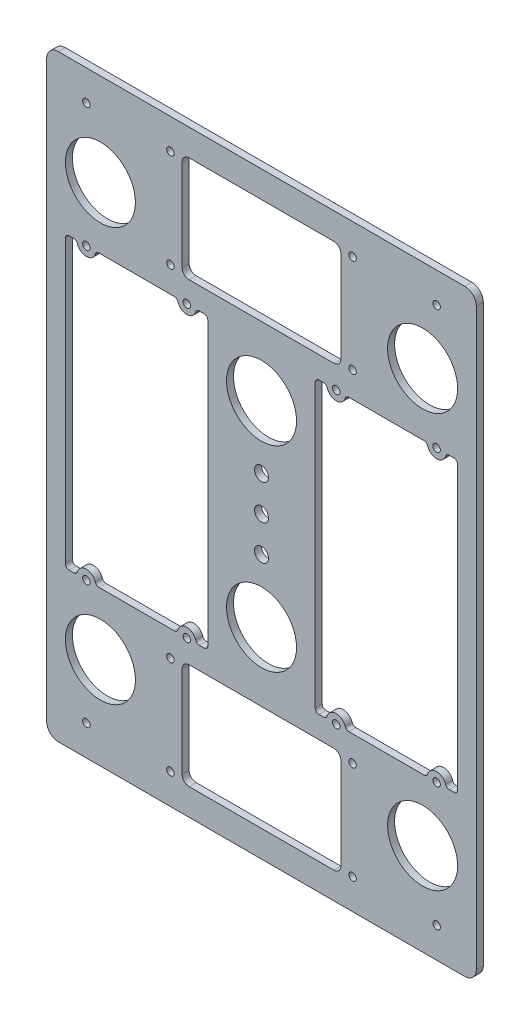
SolidWorks part; units mm, degrees
material "Thornel Mat VMA"
ref_plane "Front Plane" through (0, 0, 0) normal (0, 0, 1) x (1, 0, 0)
ref_plane "Top Plane" through (0, 0, 0) normal (0, 1, 0) x (1, 0, 0)
ref_plane "Right Plane" through (0, 0, 0) normal (1, 0, 0) x (0, 0, -1)
sketch "Model" plane through (0, 0, 0) normal (0, 0, 1) x (1, 0, 0)
  line L0 (-80.3666, 62) -> (-82.4, 62)
  line L1 (-84, 60.4) -> (-84, -60.4)
  line L2 (-82.4, -62) -> (-80.3666, -62)
  line L3 (-69.6334, 62) -> (-37.3666, 62)
  line L4 (-26.6334, 62) -> (-24.6, 62)
  line L5 (-23, 60.4) -> (-23, -60.4)
  line L6 (-24.6, -62) -> (-26.6334, -62)
  line L7 (-69.6334, -62) -> (-37.3666, -62)
  line L8 (26.6334, 62) -> (24.6, 62)
  line L9 (23, 60.4) -> (23, -60.4)
  line L10 (24.6, -62) -> (26.6334, -62)
  line L11 (37.3666, 62) -> (69.6334, 62)
  line L12 (80.3666, 62) -> (82.4, 62)
  line L13 (84, 60.4) -> (84, -60.4)
  line L14 (82.4, -62) -> (80.3666, -62)
  line L15 (37.3666, -62) -> (69.6334, -62)
  line L16 (34, 113.6) -> (34, 74.4)
  line L17 (31, 71.4) -> (-31, 71.4)
  line L18 (31, 116.6) -> (-31, 116.6)
  line L19 (-34, 74.4) -> (-34, 113.6)
  line L20 (34, -113.6) -> (34, -74.4)
  line L21 (31, -71.4) -> (-31, -71.4)
  line L22 (31, -116.6) -> (-31, -116.6)
  line L23 (-34, -74.4) -> (-34, -113.6)
  line L24 (-87, -128) -> (87, -128)
  line L25 (92, -123) -> (92, 123)
  line L26 (87, 128) -> (-87, 128)
  line L27 (-92, 123) -> (-92, -123)
  circle A0 centre (-75, 62) radius 1.6
  circle A1 centre (-32, 62) radius 1.6
  circle A2 centre (-75, -62) radius 1.6
  circle A3 centre (-32, -62) radius 1.6
  arc A4 (-78.8333, 60.8571) -> (-71.1667, 60.8571) centre (-75, 62) ccw
  arc A5 (-69.6334, 62) -> (-71.1667, 60.8571) centre (-69.6334, 60.4) ccw
  arc A6 (-78.8333, 60.8571) -> (-80.3666, 62) centre (-80.3666, 60.4) ccw
  arc A7 (-35.8333, 60.8571) -> (-28.1667, 60.8571) centre (-32, 62) ccw
  arc A8 (-26.6334, 62) -> (-28.1667, 60.8571) centre (-26.6334, 60.4) ccw
  arc A9 (-35.8333, 60.8571) -> (-37.3666, 62) centre (-37.3666, 60.4) ccw
  arc A10 (-71.1667, -60.8571) -> (-78.8333, -60.8571) centre (-75, -62) ccw
  arc A11 (-71.1667, -60.8571) -> (-69.6334, -62) centre (-69.6334, -60.4) ccw
  arc A12 (-80.3666, -62) -> (-78.8333, -60.8571) centre (-80.3666, -60.4) ccw
  arc A13 (-28.1667, -60.8571) -> (-35.8333, -60.8571) centre (-32, -62) ccw
  arc A14 (-28.1667, -60.8571) -> (-26.6334, -62) centre (-26.6334, -60.4) ccw
  arc A15 (-37.3666, -62) -> (-35.8333, -60.8571) centre (-37.3666, -60.4) ccw
  arc A16 (-84, -60.4) -> (-82.4, -62) centre (-82.4, -60.4) ccw
  arc A17 (-82.4, 62) -> (-84, 60.4) centre (-82.4, 60.4) ccw
  arc A18 (-24.6, -62) -> (-23, -60.4) centre (-24.6, -60.4) ccw
  arc A19 (-23, 60.4) -> (-24.6, 62) centre (-24.6, 60.4) ccw
  circle A20 centre (32, 62) radius 1.6
  circle A21 centre (75, 62) radius 1.6
  circle A22 centre (32, -62) radius 1.6
  circle A23 centre (75, -62) radius 1.6
  arc A24 (28.1667, 60.8571) -> (35.8333, 60.8571) centre (32, 62) ccw
  arc A25 (37.3666, 62) -> (35.8333, 60.8571) centre (37.3666, 60.4) ccw
  arc A26 (28.1667, 60.8571) -> (26.6334, 62) centre (26.6334, 60.4) ccw
  arc A27 (71.1667, 60.8571) -> (78.8333, 60.8571) centre (75, 62) ccw
  arc A28 (80.3666, 62) -> (78.8333, 60.8571) centre (80.3666, 60.4) ccw
  arc A29 (71.1667, 60.8571) -> (69.6334, 62) centre (69.6334, 60.4) ccw
  arc A30 (35.8333, -60.8571) -> (28.1667, -60.8571) centre (32, -62) ccw
  arc A31 (35.8333, -60.8571) -> (37.3666, -62) centre (37.3666, -60.4) ccw
  arc A32 (26.6334, -62) -> (28.1667, -60.8571) centre (26.6334, -60.4) ccw
  arc A33 (78.8333, -60.8571) -> (71.1667, -60.8571) centre (75, -62) ccw
  arc A34 (78.8333, -60.8571) -> (80.3666, -62) centre (80.3666, -60.4) ccw
  arc A35 (69.6334, -62) -> (71.1667, -60.8571) centre (69.6334, -60.4) ccw
  arc A36 (23, -60.4) -> (24.6, -62) centre (24.6, -60.4) ccw
  arc A37 (24.6, 62) -> (23, 60.4) centre (24.6, 60.4) ccw
  arc A38 (82.4, -62) -> (84, -60.4) centre (82.4, -60.4) ccw
  arc A39 (84, 60.4) -> (82.4, 62) centre (82.4, 60.4) ccw
  arc A40 (34, 113.6) -> (31, 116.6) centre (31, 113.6) ccw
  arc A41 (31, 71.4) -> (34, 74.4) centre (31, 74.4) ccw
  arc A42 (-34, 74.4) -> (-31, 71.4) centre (-31, 74.4) ccw
  circle A43 centre (-39, 115) radius 1.6
  circle A44 centre (-39, 73) radius 1.6
  circle A45 centre (39, 115) radius 1.6
  circle A46 centre (39, 73) radius 1.6
  arc A47 (-31, 116.6) -> (-34, 113.6) centre (-31, 113.6) ccw
  arc A48 (31, -116.6) -> (34, -113.6) centre (31, -113.6) ccw
  arc A49 (34, -74.4) -> (31, -71.4) centre (31, -74.4) ccw
  arc A50 (-31, -71.4) -> (-34, -74.4) centre (-31, -74.4) ccw
  circle A51 centre (-39, -115) radius 1.6
  circle A52 centre (-39, -73) radius 1.6
  circle A53 centre (39, -115) radius 1.6
  circle A54 centre (39, -73) radius 1.6
  arc A55 (-34, -113.6) -> (-31, -116.6) centre (-31, -113.6) ccw
  circle A56 centre (0, 0) radius 3
  circle A57 centre (0, 15) radius 3
  circle A58 centre (0, -15) radius 3
  circle A59 centre (0, 42) radius 15
  circle A60 centre (0, -42) radius 15
  circle A61 centre (-75, 115) radius 1.6
  circle A62 centre (75, 115) radius 1.6
  circle A63 centre (-75, -115) radius 1.6
  circle A64 centre (75, -115) radius 1.6
  circle A65 centre (-69, 88.5) radius 15
  circle A66 centre (69, 88.5) radius 15
  circle A67 centre (-69, -88.5) radius 15
  circle A68 centre (69, -88.5) radius 15
  arc A69 (87, -128) -> (92, -123) centre (87, -123) ccw
  arc A70 (92, 123) -> (87, 128) centre (87, 123) ccw
  arc A71 (-92, -123) -> (-87, -128) centre (-87, -123) ccw
  arc A72 (-87, 128) -> (-92, 123) centre (-87, 123) ccw
extrude "Boss-Extrude1" add sketch "Model" along normal mid plane 3
